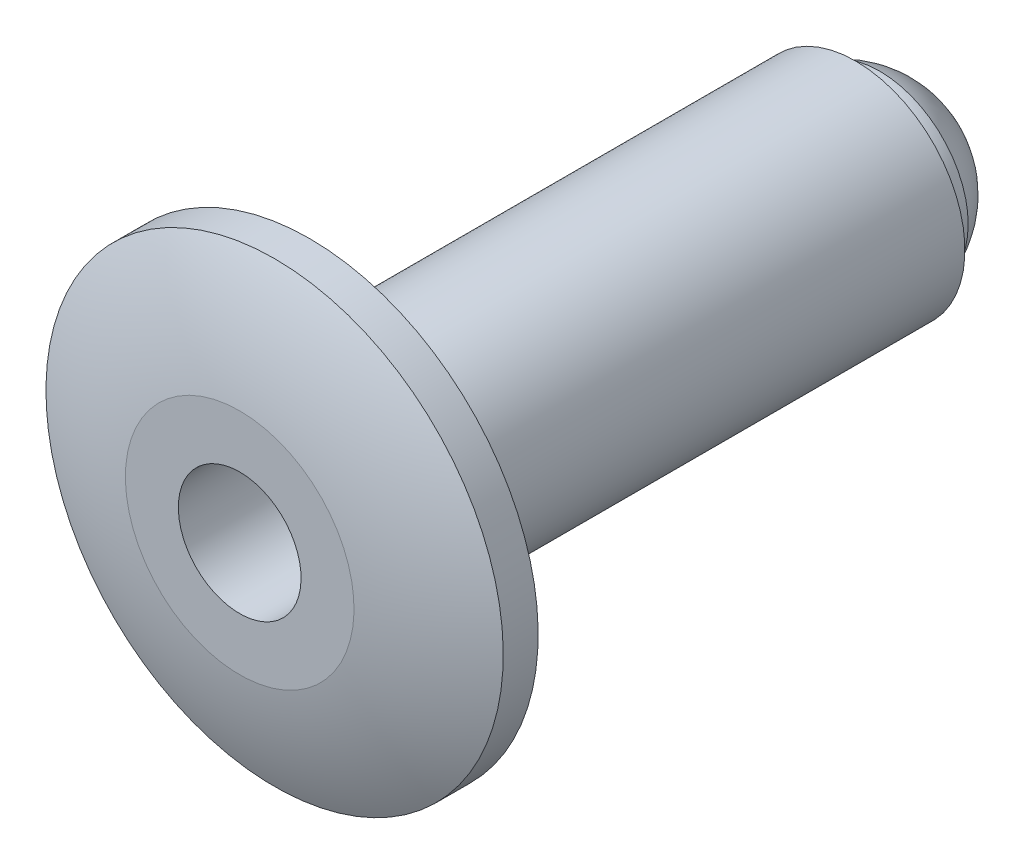
SolidWorks part; units mm, degrees
ref_plane "Front" through (0, 0, 0) normal (0, 0, 1) x (1, 0, 0)
ref_plane "Top" through (0, 0, 0) normal (0, 1, 0) x (1, 0, 0)
ref_plane "Right" through (0, 0, 0) normal (1, 0, 0) x (0, 0, -1)
sketch "Sketch1" plane through (0, 0, 0) normal (1, 0, 0) x (0, 0, -1)
  line L0 (-12.9413, 0) -> (-1.016, 0) construction
  line L1 (-1.016, 0) -> (0, 0) construction
  line L2 (0, 0) -> (7.9502, 0) construction
  line L3 (7.9502, 0) -> (9.4742, 0) construction
  line L8 (0, 3.3274) -> (0, -3.3274) construction
  line L9 (7.9502, 1.5875) -> (7.9502, -1.5875) construction
  dimension "Length" = 7.9502
  dimension "Head Height" = 1.016
  dimension "D5" = 1.524
  dimension "D9" = 11.9253
  dimension "Diameter" = 3.175
  dimension "Head Diameter" = 6.6548
sketch "Sketch2" plane through (0, 0, 0) normal (1, 0, 0) x (0, 0, -1)
  line L0 (-12.9413, 0.7937) -> (-12.9413, 0) construction
  line L1 (-12.9413, 0.7937) -> (0, 0.7937) construction
  line L2 (0, 3.3274) -> (0, -3.3274) construction
  line L3 (0, 0) -> (0, 3.3274) construction
  line L4 (-1.016, 0) -> (-1.016, -1.8472) construction
  line L5 (7.9502, 1.5875) -> (0, 1.5875)
  line L6 (7.9502, 1.5875) -> (7.9502, 0) construction
  line L7 (9.4742, 0) -> (9.4742, 1.5875) construction
  line L8 (7.9502, 1.5875) -> (7.9502, 0)
  line L9 (9.4742, 1.5875) -> (7.9502, 1.5875) construction
  line L10 (-1.016, 0.893) -> (-1.016, 1.6637)
  line L11 (7.9502, 0) -> (9.4742, 0) construction
  line L12 (7.9502, 0) -> (0.795, 0)
  line L13 (-1.016, 0.7937) -> (-1.016, 0) construction
  line L14 (7.9502, 1.5875) -> (7.9502, 0) construction
  line L15 (7.9502, 1.5875) -> (7.9502, 0) construction
  line L16 (7.9502, 0) -> (7.9502, 1.5875) construction
  line L17 (7.9502, 1.5875) -> (7.9502, 0) construction
  line L18 (7.9502, 0) -> (7.9502, 1.5875) construction
  line L19 (0, 1.5875) -> (0, 3.3274)
  line L20 (-1.016, 0.893) -> (0, 0.893)
  line L21 (-12.9413, 0.893) -> (0, 0.893) construction
  line L22 (0, 3.3274) -> (-0.508, 3.3274)
  line L23 (0, 0.893) -> (0.795, 0.893)
  line L24 (0.795, 0.893) -> (0.795, 0)
  arc A0 (9.4742, 0) -> (7.9502, 1.27) centre (8.183, 0) ccw construction
  arc A2 (-0.508, 3.3274) -> (-1.016, 1.6637) centre (4.8114, 0.7937) ccw
  dimension "D3" = 0.508
  dimension "D1" = 0.7937
  dimension "D2" = 0.795
  dimension "D5" = 1.27
  dimension "D6" = 1.6637
  dimension "D4" = 0.0992
revolve "Revolve1" add sketch "Sketch2" angle 360 about L12
sketch "Sketch7" plane through (0, 0, 0) normal (1, 0, 0) x (0, 0, -1)
  line L0 (-12.1883, 0.7937) -> (0.795, 0.7937)
  line L1 (0.795, 0.893) -> (0.795, 0) construction
  line L2 (0.795, 0.7937) -> (0.795, 0)
  line L3 (0.795, 0) -> (-12.9413, 0)
  line L5 (-12.8173, 0.266) -> (-12.1883, 0.7937)
  arc A0 (-12.9413, 0) -> (-12.8173, 0.266) centre (-12.594, 0) cw
  dimension "D1" = 0.3473
  dimension "D2" = 40
revolve "Revolve2" add sketch "Sketch7" angle 360 about L0
sketch "Sketch8" plane through (0, 0, 0) normal (1, 0, 0) x (0, 0, -1)
  line L1 (7.9502, 1.27) -> (7.9502, 0)
  line L2 (7.9502, 0) -> (9.4742, 0) construction
  line L3 (9.4742, 0) -> (8.183, 0) construction
  line L4 (9.1514, 0) -> (7.9502, 0)
  line L5 (7.9502, 1.27) -> (8.2995, 1.27) construction
  arc A0 (9.4742, 0) -> (7.9502, 1.27) centre (8.183, 0) ccw construction
  arc A1 (8.2995, 1.2859) -> (7.9502, 1.27) centre (8.183, 0) ccw
  arc A2 (8.2995, 1.2859) -> (9.1514, 0) centre (7.755, 0) cw
  circle A3 centre (8.183, 0) radius 1.2912 construction
  point P7 (9.1514, 0)
  point P8 (8.8286, 0)
  point P9 (8.5058, 0)
  point P12 (8.0666, 1.27)
  point P13 (8.183, 1.27)
revolve "Revolve3" add sketch "Sketch8" angle 360 about L3
sketch "Sketch3" plane through (0, 0, 0) normal (0, 1, 0) x (1, 0, 0)
  line L0 (-0.997, -10.809) -> (-0.2209, -12.9413)
  line L1 (-0.2209, -12.9413) -> (0.2209, -12.9413)
  line L3 (0, -12.9413) -> (0, -13.4493) construction
  line L4 (0.266, -12.8173) -> (-0.266, -12.8173) construction
  line L5 (-0.997, -10.809) -> (-0.997, -13.4493)
  line L6 (-0.997, -13.4493) -> (0.997, -13.4493)
  line L7 (0.997, -13.4493) -> (0.9969, -10.809)
  line L8 (-0.7937, 0.795) -> (-0.7937, -12.1883) construction
  line L9 (0, -12.9413) -> (0, -1.016) construction
  line L10 (0.2209, -12.9413) -> (0.9969, -10.809)
  line L11 (-0.7937, -12.1883) -> (-0.266, -12.8173) construction
  arc A0 (-0.266, -12.8173) -> (0.266, -12.8173) centre (0, -12.594) ccw construction
  point P11 (-0.266, -12.8173)
  point P25 (0, -12.9413)
  dimension "D1" = 40
  dimension "D2" = 0.2032
  dimension "D3" = 0.508
extrude "Cut-Extrude1" cut sketch "Sketch3" against normal through all both and the other way through all
pattern_circular "CirPattern1" count 2 every 90 about axis through (0, 0, 12.9413) along (0, 0, -1) of "Cut-Extrude1"
sketch "Sketch9" plane through (0, 0, 0) normal (0, 1, 0) x (1, 0, 0)
  line L0 (0, -12.9413) -> (0, 19.9517) construction
  line L1 (0, 7.9502) -> (0, 9.4742) construction
  line L2 (3.3274, 0) -> (-3.3274, 0) construction
  line L3 (2.0356, 0) -> (2.1341, 0)
  line L4 (2.0356, 0) -> (2.0356, 0.0254)
  line L5 (2.0356, 0.0254) -> (2.1341, 0.0254)
  line L6 (2.1341, 0) -> (2.1341, 0.0254)
  line L8 (2.3081, 0) -> (2.4066, 0)
  line L9 (2.3081, 0) -> (2.3081, 0.0254)
  line L10 (2.3081, 0.0254) -> (2.4066, 0.0254)
  line L11 (2.4066, 0) -> (2.4066, 0.0254)
  line L12 (2.551, 0) -> (2.6495, 0)
  line L13 (2.551, 0) -> (2.551, 0.0254)
  line L14 (2.551, 0.0254) -> (2.6495, 0.0254)
  line L15 (2.6495, 0) -> (2.6495, 0.0254)
  line L16 (2.9023, 0) -> (3.0008, 0)
  line L17 (2.9023, 0) -> (2.9023, 0.0254)
  line L18 (2.9023, 0.0254) -> (3.0008, 0.0254)
  line L19 (3.0008, 0) -> (3.0008, 0.0254)
  line L20 (1.9076, 0) -> (1.8091, 0)
  line L21 (1.9076, 0) -> (1.9076, 0.0254)
  line L22 (1.9076, 0.0254) -> (1.8091, 0.0254)
  line L23 (1.8091, 0) -> (1.8091, 0.0254)
  point P24 (2.9515, 0.0254)
  point P25 (2.6003, 0.0254)
  point P26 (2.3573, 0.0254)
  point P27 (2.0848, 0.0254)
  point P32 (1.8583, 0.0254)
  dimension "D1" = 0.0985
  dimension "D2" = 0.0254
  dimension "D3" = 5.903
  dimension "D4" = 5.2005
  dimension "D5" = 4.7146
  dimension "D6" = 4.1697
  dimension "D7" = 3.7167
revolve "Revolve4" add sketch "Sketch9" angle 360 about L0
sketch "Sketch10" plane through (0, 0, 1.016) normal (0, 0, 1) x (1, 0, 0)
  circle A0 centre (0, 0) radius 0.7937
  arc A1 (0.5613, -0.5613) -> (0.5613, 0.5613) centre (0, 0) ccw construction
extrude "Cut-Extrude2" cut sketch "Sketch10" against normal up to surface (1.811 mm away) and the other way through all up to face at (0, 0.893, -0.795)
equation "\"D5@Sketch1\" = \"Head Height@Sketch1\" * 1.5"
equation "\"D9@Sketch1\" = \"Length@Sketch1\" * 1.5"
equation "\"D1@Sketch2\"=\"Diameter@Sketch1\"/4"
equation "\"D4@Sketch2\"=\"D1@Sketch2\"/8"
equation "\"D2@Sketch2\"=\"Length@Sketch1\"/10"
equation "\"D5@Sketch2\"=\"Diameter@Sketch1\"*.8/2"
equation "\"D1@Sketch7\"=(\"D1@Sketch2\"-\"D4@Sketch2\")*2*.25"
equation "\"D6@Sketch2\"=\"Head Diameter@Sketch1\"/2*.5"
equation "\"D7@Sketch9\"=.15566*(\"Head Diameter@Sketch1\"-\"Diameter@Sketch1\")+\"Diameter@Sketch1\""
equation "\"D3@Sketch9\"=.7839623*(\"Head Diameter@Sketch1\"-\"Diameter@Sketch1\")+\"Diameter@Sketch1\""
equation "\"D1@Sketch9\"=.028302*(\"Head Diameter@Sketch1\"-\"Diameter@Sketch1\")"
equation "\"D6@Sketch9\"=.285849*(\"Head Diameter@Sketch1\"-\"Diameter@Sketch1\")+\"Diameter@Sketch1\""
equation "\"D5@Sketch9\"=.4424528*(\"Head Diameter@Sketch1\"-\"Diameter@Sketch1\")+\"Diameter@Sketch1\""
equation "\"D4@Sketch9\"=.582075*(\"Head Diameter@Sketch1\"-\"Diameter@Sketch1\")+\"Diameter@Sketch1\""
